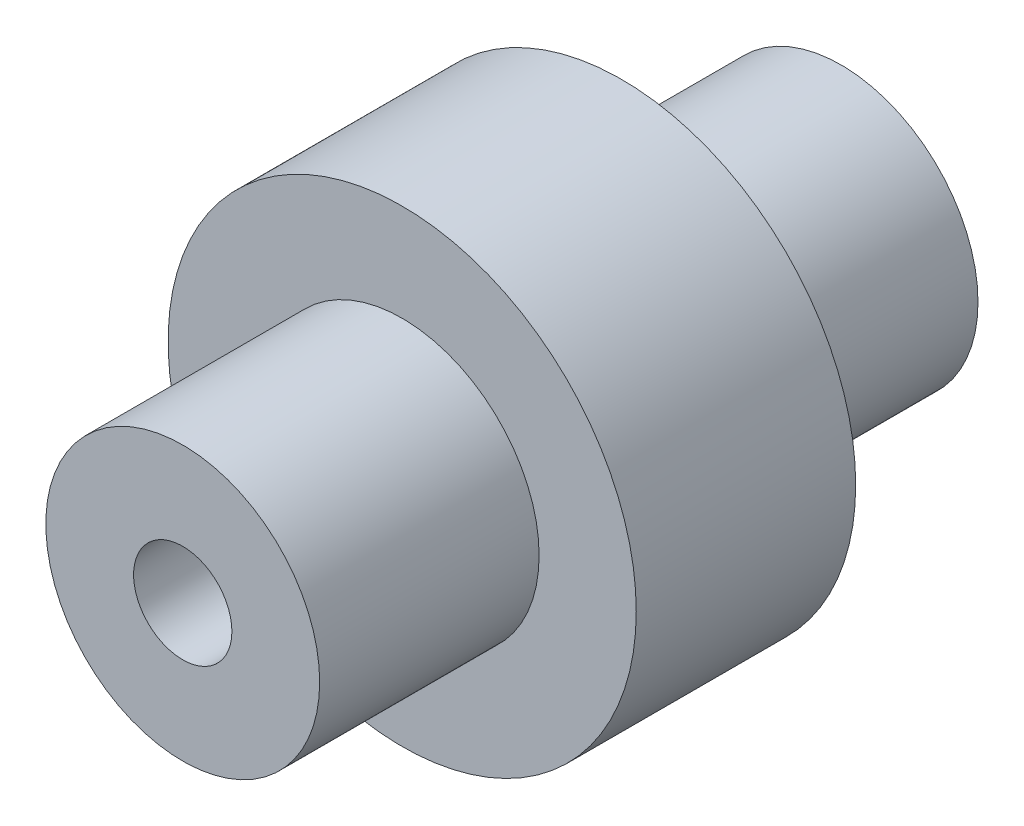
SolidWorks part; units mm, degrees
material "Titanium"
ref_plane "Front Plane" through (0, 0, 0) normal (0, 0, 1) x (1, 0, 0)
ref_plane "Top Plane" through (0, 0, 0) normal (0, 1, 0) x (1, 0, 0)
ref_plane "Right Plane" through (0, 0, 0) normal (1, 0, 0) x (0, 0, -1)
sketch "Sketch2" plane through (0, 0, 0) normal (0, 0, 1) x (1, 0, 0)
  circle A0 centre (0, 0) radius 1.872
  circle A1 centre (0, 0) radius 0.672
  dimension "D1" = 3.744
  dimension "D2" = 1.344
extrude "Boss-Extrude1" add sketch "Sketch2" along normal blind 9
sketch "Sketch3" plane through (0, 0, 0) normal (0, 0, 1) x (1, 0, 0)
  circle A0 centre (0, 0) radius 3.2
  circle A1 centre (0, 0) radius 1.872
  circle A2 centre (0, 0) radius 1.872 construction
  dimension "D1" = 6.4
extrude "Boss-Extrude2" add sketch "Sketch3" along direction (0, 0, 1) on the side of the normal blind 3 from offset 3
equation "\"bScale\"= 8"
equation "\"lScale\"= 8"
equation "\"D1@Sketch2\"=.4680mm*\"bScale\""
equation "\"D2@Sketch2\"=.1680mm*\"bScale\""
equation "\"D1@Sketch3\"=\"bScale\"*0.8"
